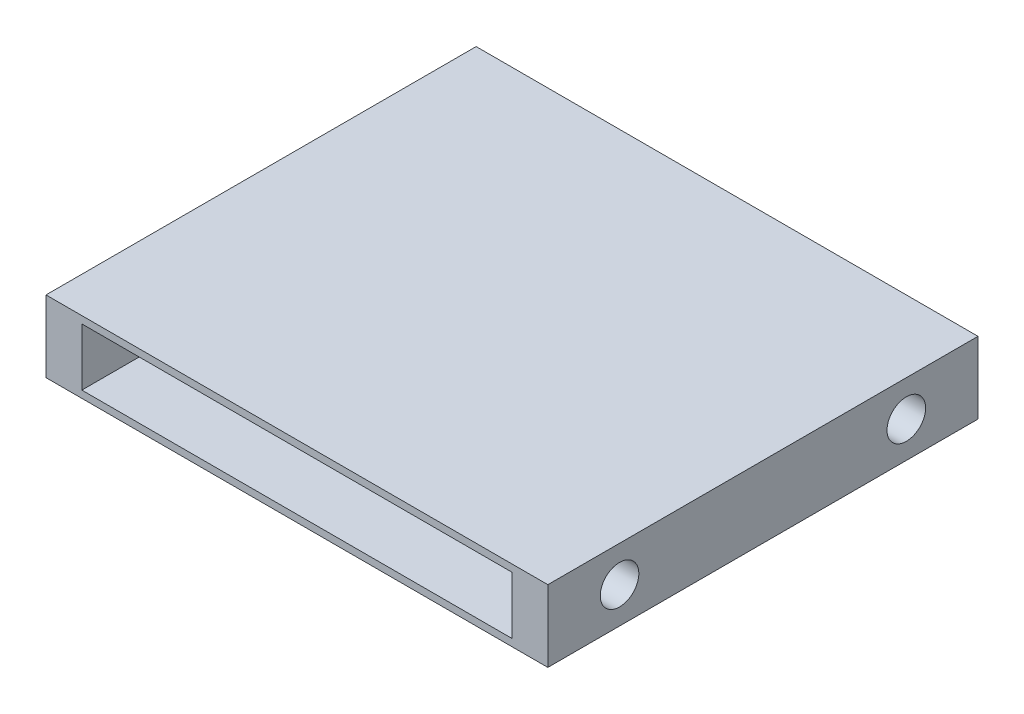
SolidWorks part; units mm, degrees
ref_plane "Front Plane" through (0, 0, 0) normal (0, 0, 1) x (1, 0, 0)
ref_plane "Top Plane" through (0, 0, 0) normal (0, 1, 0) x (1, 0, 0)
ref_plane "Right Plane" through (0, 0, 0) normal (1, 0, 0) x (0, 0, -1)
sketch "Sketch1" plane through (0, 0, 0) normal (0, 1, 0) x (1, 0, 0)
  line L1 (0, 0) -> (70, 0)
  line L2 (0, 0) -> (0, -60)
  line L3 (0, -60) -> (70, -60)
  line L4 (70, 0) -> (70, -60)
  dimension "D1" = 70
  dimension "D2" = 60
extrude "Boss-Extrude1" add sketch "Sketch1" along normal blind 10
sketch "Sketch2" plane through (0, 0, 60) normal (0, 0, 1) x (1, 0, 0)
  line L0 (0, 10) -> (0, 0) construction
  line L1 (5, 9) -> (65, 9)
  line L2 (5, 9) -> (5, 1)
  line L3 (5, 1) -> (65, 1)
  line L4 (65, 9) -> (65, 1)
  line L5 (70, 10) -> (70, 0) construction
  line L6 (0, 0) -> (70, 0) construction
  dimension "D1" = 5
  dimension "D2" = 5
  dimension "D3" = 8
  dimension "D4" = 1
extrude "Cut-Extrude1" cut sketch "Sketch2" against normal blind 55
sketch "Sketch3" plane through (65, 0, 0) normal (-1, 0, 0) x (0, 0, 1)
  line L0 (5, 1) -> (5, 9) construction
  line L1 (5, 1) -> (60, 1) construction
  circle A0 centre (10, 5) radius 2.6898
  point P4 (0, 0)
  point P6 (61.4732, -0.3259)
  dimension "D1" = 5
  dimension "D2" = 4
extrude "Cut-Extrude2" cut sketch "Sketch3" against normal blind 55
ref_plane "Plane1" through (0, 0, 30) normal (0, 0, 1) x (1, 0, 0)
ref_plane "Plane2" through (35, 0, 0) normal (-1, 0, 0) x (0, 0, 1)
mirror "Mirror1" about plane through (35, 0, 0) normal (-1, 0, 0) of "Cut-Extrude2"
mirror "Mirror2" about plane through (0, 0, 30) normal (0, 0, 1) of "Mirror1", "Cut-Extrude2"
